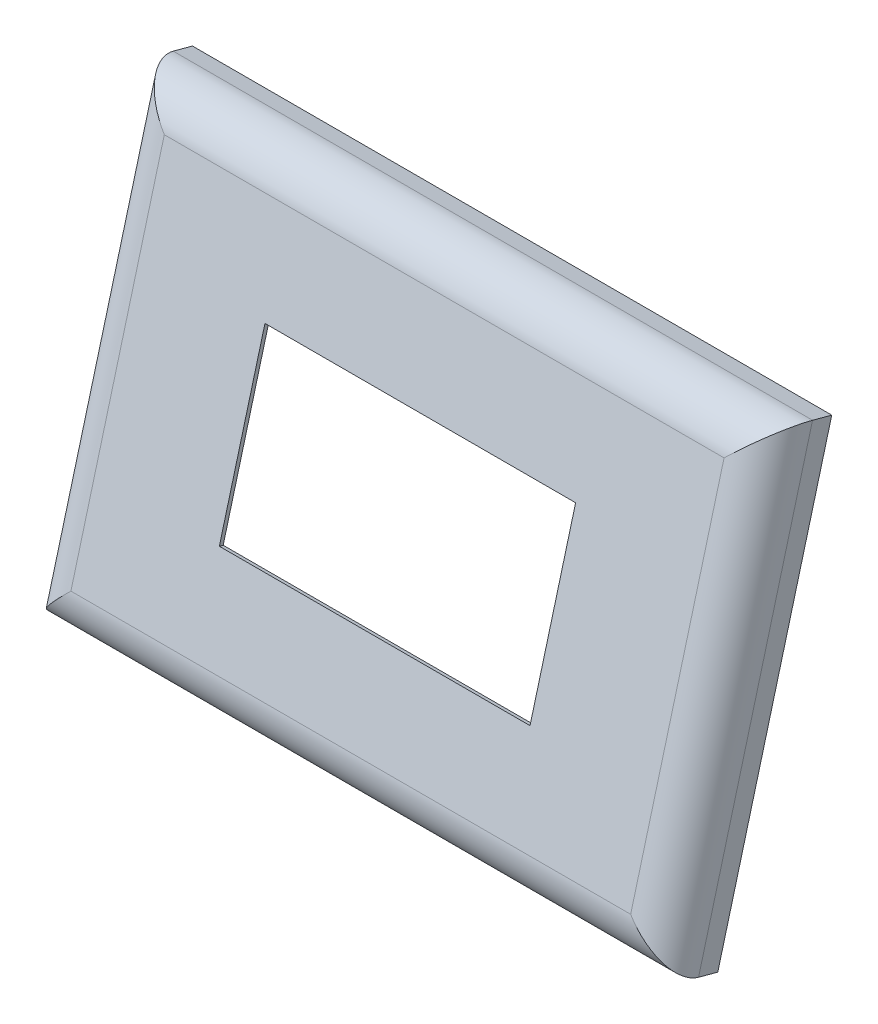
SolidWorks part; units mm, degrees
ref_plane "Front Plane" through (0, 0, 0) normal (0, 0, 1) x (1, 0, 0)
ref_plane "Top Plane" through (0, 0, 0) normal (0, 1, 0) x (1, 0, 0)
ref_plane "Right Plane" through (0, 0, 0) normal (1, 0, 0) x (0, 0, -1)
sketch "Sketch1" plane through (0, -69.6731, -260.0235) normal (0, 0.2588, 0.9659) x (1, 0, 0)
  line L0 (1180.9293, 658.266) -> (1165.6506, 658.266) construction
  line L1 (874.772, 658.266) -> (859.4933, 658.266) construction
  line L2 (1116.2079, 658.266) -> (924.2147, 658.266) construction
  line L3 (859.4933, 658.266) -> (859.4933, 436.8301) construction
  line L5 (1180.9293, 436.8301) -> (1180.9293, 658.266) construction
  line L6 (1180.9293, 658.266) -> (1165.6506, 658.266) construction
  line L7 (874.772, 658.266) -> (859.4933, 658.266) construction
  line L8 (1116.2079, 658.266) -> (924.2147, 658.266) construction
  line L9 (859.4933, 658.266) -> (859.4933, 436.8301) construction
  line L10 (859.4933, 436.8301) -> (1180.9293, 436.8301) construction
  line L11 (1180.9293, 436.8301) -> (1180.9293, 658.266) construction
  line L13 (859.4933, 658.266) -> (1180.9293, 658.266)
  line L14 (859.4933, 658.266) -> (859.4933, 436.8301)
  line L15 (859.4933, 436.8301) -> (1180.9293, 436.8301)
  line L16 (1180.9293, 658.266) -> (1180.9293, 436.8301)
extrude "Boss-Extrude1" add sketch "Sketch1" along normal blind 30
fillet "Fillet1" radius 20 4 edges at (1020.2113, 360.0369, -344.1057) (1180.9293, 466.9823, -372.7616) (859.4933, 466.9823, -372.7616) (1020.2113, 573.9276, -401.4175)
shell "Shell1" thickness 2
sketch "Sketch2" plane through (0, -61.9085, -231.0457) normal (0, 0.2588, 0.9659) x (1, 0, 0)
  line L0 (1020.2113, 638.266) -> (1020.2113, 456.8301) construction
  line L1 (942.1113, 591.8481) -> (1098.3113, 591.8481)
  line L2 (942.1113, 591.8481) -> (942.1113, 503.2481)
  line L3 (942.1113, 503.2481) -> (1098.3113, 503.2481)
  line L4 (1098.3113, 591.8481) -> (1098.3113, 503.2481)
  line L5 (1160.9293, 638.266) -> (879.4933, 638.266) construction
  line L6 (879.4933, 456.8301) -> (1160.9293, 456.8301) construction
  line L7 (879.4933, 638.266) -> (879.4933, 456.8301) construction
  point P10 (1020.2113, 591.8481)
  point P11 (942.1113, 547.5481)
  point P14 (879.4933, 547.5481)
  dimension "D1" = 156.2
  dimension "D2" = 88.6
extrude "Cut-Extrude1" cut sketch "Sketch2" against normal up to next
sketch "Sketch5" plane through (0, -62.4262, -232.9776) normal (0, -0.2588, -0.9659) x (-1, 0, 0)
  circle A0 centre (-901.3945, 616.3649) radius 3 construction
  circle A1 centre (-901.3945, 616.3649) radius 3 construction
  circle A2 centre (-901.3945, 478.7312) radius 3 construction
  circle A3 centre (-901.3945, 478.7312) radius 3 construction
  circle A4 centre (-1139.0281, 616.3649) radius 3 construction
  circle A5 centre (-1139.0281, 616.3649) radius 3 construction
  circle A6 centre (-1139.0281, 478.7312) radius 3 construction
  circle A7 centre (-1139.0281, 478.7312) radius 3 construction
  circle A8 centre (-901.3945, 616.3649) radius 5
  circle A9 centre (-901.3945, 478.7312) radius 5
  circle A10 centre (-1139.0281, 478.7312) radius 5
  circle A11 centre (-1139.0281, 616.3649) radius 5
  circle A12 centre (-1139.0281, 616.3649) radius 1.5
  circle A13 centre (-1139.0281, 478.7312) radius 1.5
  circle A14 centre (-901.3945, 478.7312) radius 1.5
  circle A15 centre (-901.3945, 616.3649) radius 1.5
  dimension "D1" = 10
  dimension "D2" = 10
  dimension "D3" = 10
  dimension "D4" = 10
  dimension "D5" = 3
extrude "Boss-Extrude2" add sketch "Sketch5" along normal blind 20
fillet "Fillet2" radius 5 4 edges at (901.3945, 395.1631, -355.5882) (901.3945, 528.107, -391.2105) (1139.0281, 395.1631, -355.5882) (1139.0281, 528.107, -391.2105)
